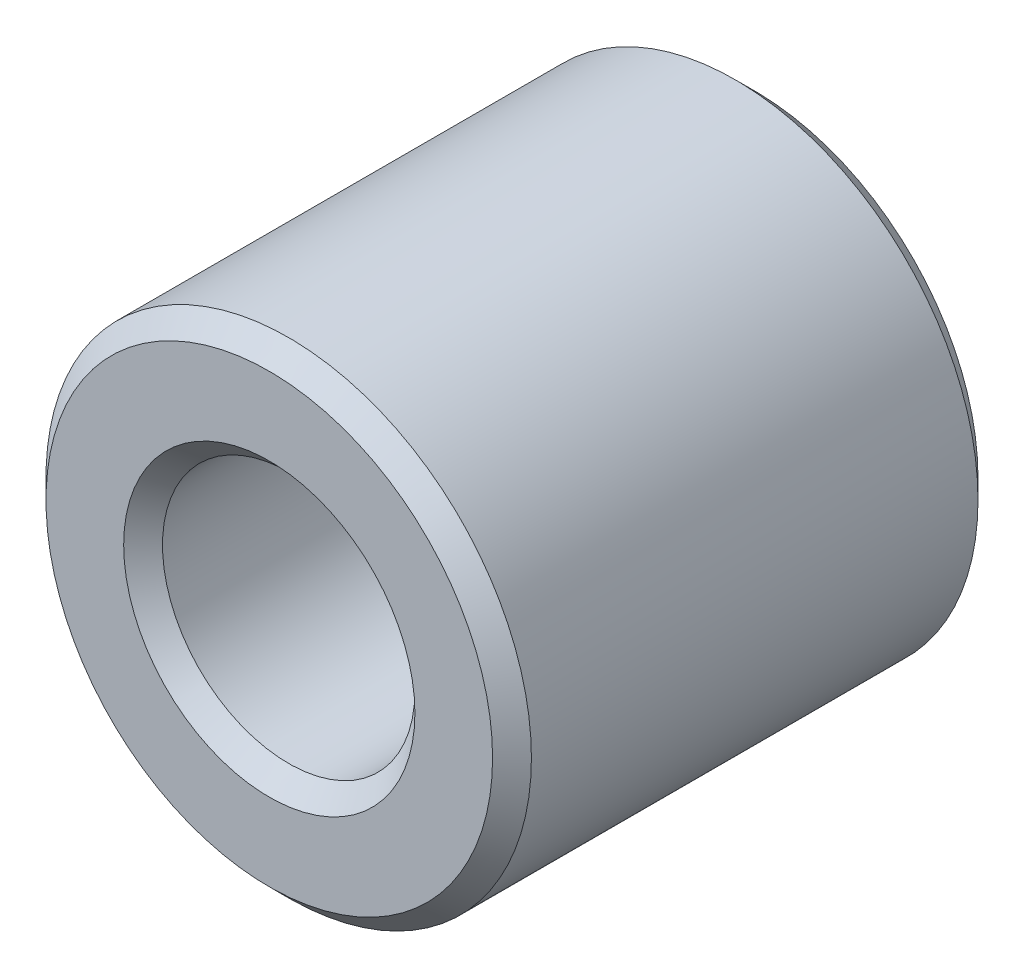
SolidWorks part; units mm, degrees
material "Tin Bearing Bronze"
ref_plane "Front Plane" through (0, 0, 0) normal (0, 0, 1) x (1, 0, 0)
ref_plane "Top Plane" through (0, 0, 0) normal (0, 1, 0) x (1, 0, 0)
ref_plane "Right Plane" through (0, 0, 0) normal (1, 0, 0) x (0, 0, -1)
sketch "Sketch1" plane through (0, 0, 0) normal (0, 0, 1) x (1, 0, 0)
  circle A0 centre (0, 0) radius 3.175
  circle A1 centre (0, 0) radius 1.651
  dimension "D1" = 3.302
  dimension "D2" = 6.35
extrude "Boss-Extrude1" add sketch "Sketch1" along normal blind 6.35
chamfer "Chamfer1" distance 0.254 angle 45 4 edges at (3.175, 0, 0) (1.651, 0, 0) (3.175, 0, 6.35) (1.651, 0, 6.35)
equation "\"ID\"= 0.125"
equation "\"OD\"= 0.25"
equation "\"L\"= 0.25"
